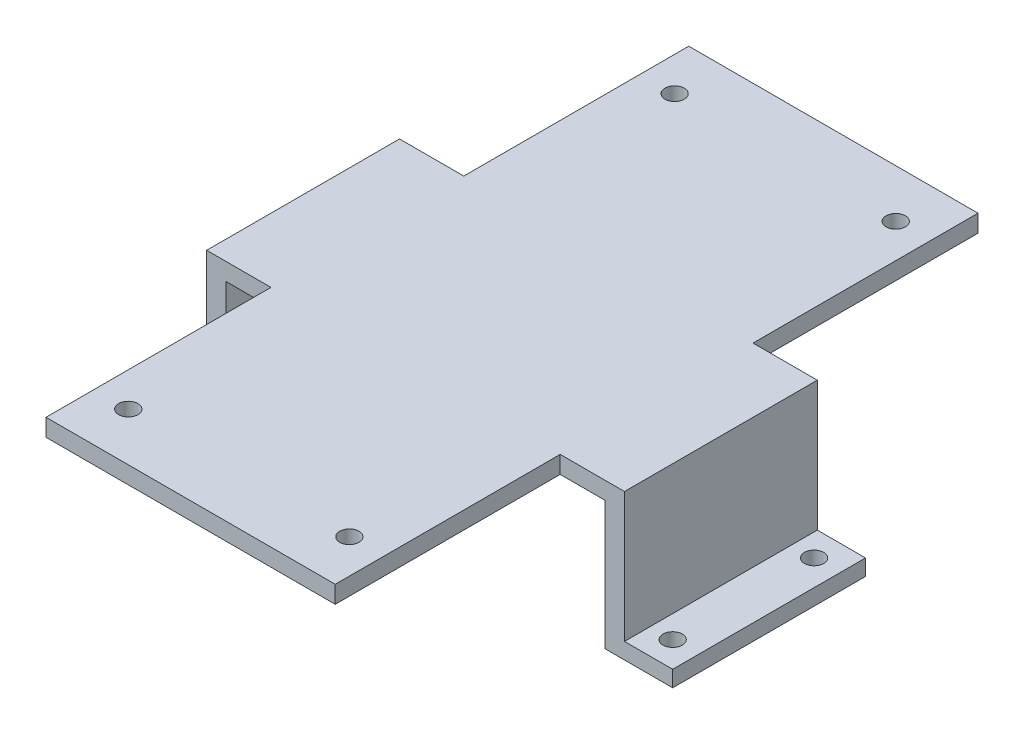
SolidWorks part; units mm, degrees
ref_plane "Front Plane" through (0, 0, 0) normal (0, 0, 1) x (1, 0, 0)
ref_plane "Top Plane" through (0, 0, 0) normal (0, 1, 0) x (1, 0, 0)
ref_plane "Right Plane" through (0, 0, 0) normal (1, 0, 0) x (0, 0, -1)
sketch "Sketch1" plane through (0, 0, 0) normal (0, 1, 0) x (1, 0, 0)
  line L1 (0, 0) -> (-45, 0)
  line L2 (0, 0) -> (0, 100)
  line L3 (0, 100) -> (-45, 100)
  line L4 (-45, 0) -> (-45, 100)
  dimension "D1" = 100
  dimension "D2" = 45
extrude "Boss-Extrude1" add sketch "Sketch1" along normal blind 2.7017
sketch "Sketch2" plane through (0, 2.7017, 0) normal (0, 1, 0) x (1, 0, 0)
  line L0 (0, 100) -> (-45, 100) construction
  line L1 (-45, 100) -> (-45, 0) construction
  circle A0 centre (-39.7, 92.5) radius 1.5
  dimension "D1" = 3
  dimension "D2" = 7.5
  dimension "D3" = 5.3
extrude "Cut-Extrude1" cut sketch "Sketch2" against normal up to surface (2.7017 mm away) contours A0 up to face at (-22.5, 0, -50)
pattern_linear "LPattern1" count 2 spacing 85 along (0, 0, 1) count 2 spacing 34.4 along (1, 0, 0) of "Cut-Extrude1"
sketch "Sketch4" plane through (0, 0, 0) normal (1, 0, 0) x (0, 0, -1)
  line L0 (0, 2.7017) -> (100, 2.7017) construction
  line L1 (35, 2.7017) -> (65, 2.7017)
  line L2 (35, 2.7017) -> (35, 0)
  line L3 (35, 0) -> (65, 0)
  line L4 (65, 2.7017) -> (65, 0)
  line L5 (0, 0) -> (100, 0) construction
  line L6 (0, 44.2539) -> (0, -44.2539) construction
  dimension "D1" = 30
  dimension "D2" = 35
extrude "Boss-Extrude2" add sketch "Sketch4" along normal blind 10
sketch "Sketch6" plane through (0, 0, 0) normal (0, -1, 0) x (1, 0, 0)
  line L0 (10, -65) -> (0, -65) construction
  line L1 (10, -35) -> (7, -35)
  line L2 (10, -35) -> (10, -65)
  line L3 (10, -65) -> (7, -65)
  line L4 (7, -35) -> (7, -65)
  point P4 (0, 0)
  point P8 (0, 0)
  dimension "D1" = 3
extrude "Boss-Extrude3" add sketch "Sketch6" along normal blind 20
sketch "Sketch7" plane through (10, 0, 0) normal (1, 0, 0) x (0, 0, -1)
  line L0 (65, -20) -> (65, 2.7017) construction
  line L1 (35, -20) -> (65, -20)
  line L2 (35, -20) -> (35, -17.5)
  line L3 (35, -17.5) -> (65, -17.5)
  line L4 (65, -20) -> (65, -17.5)
  dimension "D1" = 2.5
extrude "Boss-Extrude4" add sketch "Sketch7" along normal blind 7.5
sketch "Sketch13" plane through (0, 2.7017, 0) normal (0, 1, 0) x (1, 0, 0)
  line L0 (-22.5, 100) -> (-22.5, 0) construction
  line L1 (0, 100) -> (-45, 100) construction
  line L2 (-44.2539, 0) -> (44.2539, 0) construction
ref_plane "Plane1" through (-22.5, 0, 0) normal (-1, 0, 0) x (0, 0, 1)
mirror "Mirror2" about plane through (-22.5, 0, 0) normal (-1, 0, 0) of "Boss-Extrude2"
sketch "Sketch14" plane through (0, 0, 0) normal (0, -1, 0) x (1, 0, 0)
  line L0 (-55, -65) -> (-45, -65) construction
  line L1 (-55, -35) -> (-52, -35)
  line L2 (-55, -35) -> (-55, -65)
  line L3 (-55, -65) -> (-52, -65)
  line L4 (-52, -35) -> (-52, -65)
  dimension "D1" = 3
extrude "Boss-Extrude5" add sketch "Sketch14" along normal blind 20
sketch "Sketch15" plane through (-55, 0, 0) normal (-1, 0, 0) x (0, 0, 1)
  line L1 (-65, -20) -> (-35, -20)
  line L2 (-65, -20) -> (-65, -17.5)
  line L3 (-65, -17.5) -> (-35, -17.5)
  line L4 (-35, -20) -> (-35, -17.5)
extrude "Boss-Extrude6" add sketch "Sketch15" along normal blind 7.5 contours L2 L1 L4 L3
sketch "Sketch16" plane through (0, -17.5, 0) normal (0, 1, 0) x (1, 0, 0)
  line L0 (-62.5, 65) -> (-55, 65) construction
  line L1 (-62.5, 65) -> (-62.5, 35) construction
  circle A0 centre (-58.5, 61) radius 1.5
  dimension "D1" = 3
  dimension "D2" = 4
  dimension "D3" = 4
extrude "Cut-Extrude2" cut sketch "Sketch16" against normal up to surface (2.5 mm away) up to face at (-57.25, -20, -50)
pattern_linear "LPattern2" count 2 spacing 22 along (0, 0, 1) count 2 spacing 72 along (1, 0, 0) of "Cut-Extrude2"
sketch "Sketch17" plane through (0, 0, 0) normal (0, -1, 0) x (1, 0, 0)
  line L0 (-62.5, -50) -> (17.5, -50) construction
  line L1 (-62.5, -65) -> (-62.5, -35) construction
  line L2 (17.5, -35) -> (17.5, -65) construction
  point P6 (0, 0)
ref_plane "Plane3" through (0, 0, -50) normal (0, 0, -1) x (1, 0, 0)
